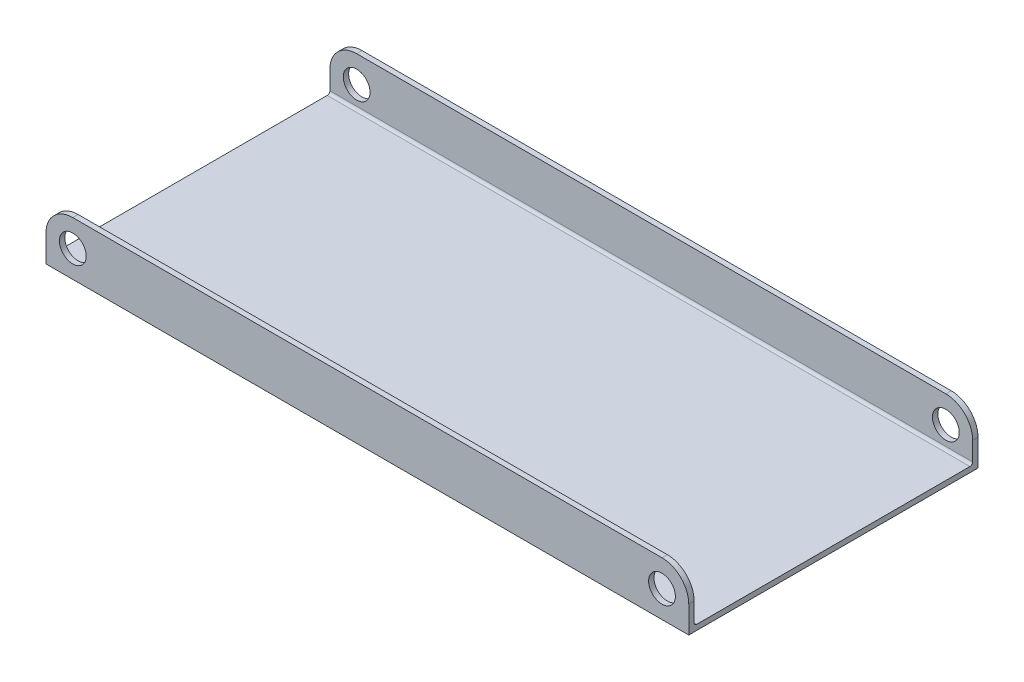
SolidWorks part; units mm, degrees
ref_plane "Front Plane" through (0, 0, 0) normal (0, 0, 1) x (1, 0, 0)
ref_plane "Top Plane" through (0, 0, 0) normal (0, 1, 0) x (1, 0, 0)
ref_plane "Right Plane" through (0, 0, 0) normal (1, 0, 0) x (0, 0, -1)
sketch "Sketch2" plane through (0, 0, 0) normal (0, 1, 0) x (1, 0, 0)
  line L1 (-76.2, 34.29) -> (76.2, 34.29)
  line L2 (-76.2, 34.29) -> (-76.2, -34.29)
  line L3 (-76.2, -34.29) -> (76.2, -34.29)
  line L4 (76.2, 34.29) -> (76.2, -34.29)
  line L5 (-76.2, 34.29) -> (76.2, -34.29) construction
  line L6 (-76.2, -34.29) -> (76.2, 34.29) construction
  point P0 (0, 0)
  dimension "D1" = 152.4
  dimension "D2" = 68.58
extrude "Boss-Extrude1" add sketch "Sketch2" along normal blind 12.7
sketch "Sketch3" plane through (0, 12.7, 0) normal (0, 1, 0) x (1, 0, 0)
  line L0 (-76.2, -33.02) -> (76.2, -33.02)
  line L1 (-76.2, 34.29) -> (-76.2, -34.29) construction
  line L2 (76.2, -34.29) -> (76.2, 34.29) construction
  line L3 (-76.2, -34.29) -> (76.2, -34.29) construction
  line L4 (0, 0) -> (11.6033, 0)
  line L5 (-76.2, 33.02) -> (76.2, 33.02)
  line L6 (-76.2, 33.02) -> (-76.2, 34.29)
  line L7 (-76.2, 34.29) -> (76.2, 34.29)
  line L8 (76.2, 34.29) -> (76.2, 33.02)
  dimension "D1" = 1.27
extrude "Cut-Extrude1" cut sketch "Sketch3" against normal blind 11.43
sketch "Sketch4" plane through (0, 0, 34.29) normal (0, 0, 1) x (1, 0, 0)
  line L0 (-76.2, 12.7) -> (-76.2, 0) construction
  line L1 (-76.2, 12.7) -> (76.2, 12.7) construction
  line L2 (0, 0) -> (0, 7.7512) construction
  line L3 (-76.2, 0) -> (76.2, 0) construction
  line L4 (-76.2, 6.35) -> (-76.2, 12.7)
  line L5 (-69.85, 12.7) -> (69.85, 12.7)
  line L6 (-76.2, 6.35) -> (-76.2, 0)
  line L7 (-76.2, 0) -> (76.2, 0)
  line L8 (76.2, 6.35) -> (76.2, 0)
  line L9 (-76.2, 12.7) -> (-69.85, 12.7)
  line L10 (-69.85, 12.7) -> (-69.6514, 12.9009)
  line L11 (69.85, 12.7) -> (76.2, 12.7)
  line L12 (76.2, 12.7) -> (76.2, 6.35)
  line L13 (76.2, 6.35) -> (76.3519, 6.4258)
  circle A0 centre (-69.85, 6.35) radius 3.175
  arc A1 (-69.85, 12.7) -> (-76.2, 6.35) centre (-69.85, 6.35) ccw
  arc A2 (69.85, 12.7) -> (76.2, 6.35) centre (69.85, 6.35) cw
  circle A3 centre (69.85, 6.35) radius 3.175
  point P18 (-76.2, 12.7)
  line M4 (76.2, 0) -> (76.2, 12.7)
  line M5 (76.2, 12.7) -> (-76.2, 12.7)
  line M6 (-76.2, 12.7) -> (-76.2, 0)
  dimension "D3" = 6.35
  dimension "D4" = 6.35
  dimension "D5" = 6.35
  dimension "D1" = 6.35
  dimension "D2" = 6.35
extrude "Cut-Extrude2" cut sketch "Sketch4" against normal through all contours A1 M5 M6 | A0 | A3 | A2 M5 M4
fillet "Fillet1" radius 0.635 2 edges at (0, 1.27, 33.02) (0, 1.27, -33.02)
